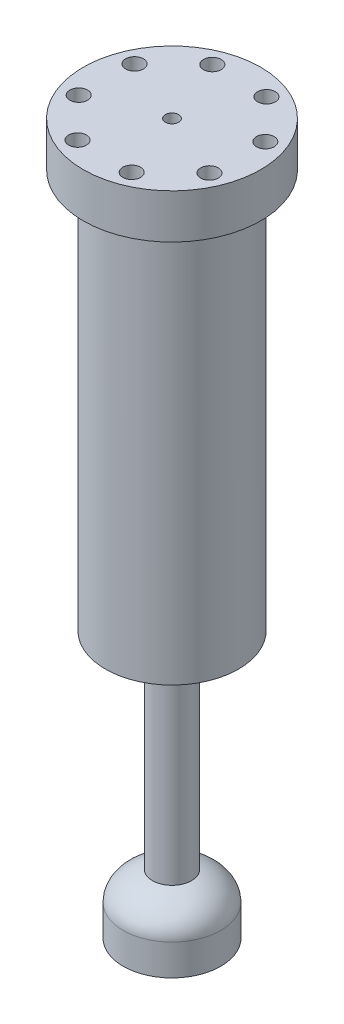
SolidWorks part; units mm, degrees
ref_plane "Front Plane" through (0, 0, 0) normal (0, 0, 1) x (1, 0, 0)
ref_plane "Top Plane" through (0, 0, 0) normal (0, 1, 0) x (1, 0, 0)
ref_plane "Right Plane" through (0, 0, 0) normal (1, 0, 0) x (0, 0, -1)
sketch "Sketch1" plane through (0, 0, 0) normal (1, 0, 0) x (0, 0, -1)
  line L6 (0, 80) -> (10, 80)
  line L7 (10, 80) -> (10, 75)
  line L8 (10, 75) -> (7.5, 75)
  line L9 (5.5, 3.5) -> (5.5, 0)
  line L10 (4.5, 0) -> (5.5, 0)
  line L11 (2.2, 30) -> (2.2, 6.7078)
  line L12 (7.5, 75) -> (7.5, 30)
  line L13 (7.5, 30) -> (2.2, 30)
  line L15 (4.5, 3.5) -> (4.5, 1)
  line L16 (1.9324, 5.7443) -> (0, 5.7443)
  line L17 (0, 5.7443) -> (0, 80)
  line L18 (4.5, 1) -> (4.5, 0)
  line L19 (0, 0) -> (5.5, 0) construction
  line L20 (0, 1) -> (4.5, 1) construction
  ellipse E0 centre (0, 3.5) end of major axis (-5.5, 3.5) minor radius 3.5 (5.5, 3.5) -> (2.2, 6.7078) ccw
  spline S0 degree 1 poles (4.5, 3.5) (1.9324, 5.7443) knots 0 0 1 1 construction
  spline S1 degree 3 poles (4.5, 3.5) (4.5, 3.6972) (4.4202, 4.0582) (3.9701, 4.7059) (3.2676, 5.216) (2.5506, 5.5494) (2.1371, 5.6874) (1.9324, 5.7443) knots 3.141593 3.141593 3.141593 3.141593 3.431413 3.721232 4.011052 4.155962 4.300872 4.300872 4.300872 4.300872
  point P3 (10, 77.5)
  dimension "D5" = 3.5
  dimension "D1" = 74.2557
  dimension "D2" = 2.5
  dimension "D3" = 10
  dimension "D6" = 45
revolve "Revolve1" add sketch "Sketch1" angle 360 about L17
sketch "Sketch3" plane through (0, 5.7443, 0) normal (0, -1, 0) x (1, 0, 0)
  circle A0 centre (0, 0) radius 0.75
  dimension "D1" = 1.5
extrude "Cut-Extrude1" cut sketch "Sketch3" against normal blind 75
sketch "Sketch4" plane through (0, 80, 0) normal (0, 1, 0) x (1, 0, 0)
  circle A0 centre (-2.9856, 7.5283) radius 1
  circle A1 centre (3.2122, 7.4344) radius 1
  circle A2 centre (7.5283, 2.9856) radius 1
  circle A3 centre (7.4344, -3.2122) radius 1
  circle A4 centre (2.9856, -7.5283) radius 1
  circle A5 centre (-3.2122, -7.4344) radius 1
  circle A6 centre (-7.5283, -2.9856) radius 1
  circle A7 centre (-7.4344, 3.2122) radius 1
  point P19 (0, 0)
  dimension "D1" = 2
  dimension "D2" = 8
extrude "Cut-Extrude2" cut sketch "Sketch4" against normal blind 5
